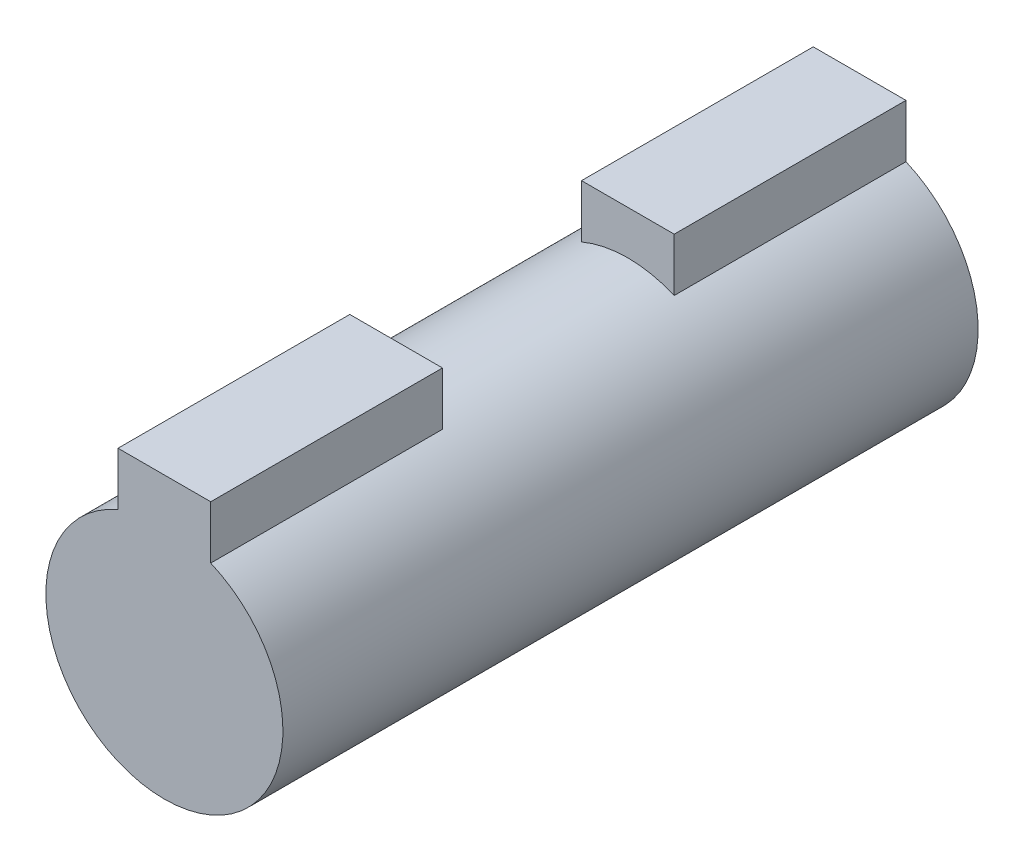
SolidWorks part; units mm, degrees
ref_plane "Front" through (0, 0, 0) normal (0, 0, 1) x (1, 0, 0)
ref_plane "Top" through (0, 0, 0) normal (0, 1, 0) x (1, 0, 0)
ref_plane "Right" through (0, 0, 0) normal (1, 0, 0) x (0, 0, -1)
sketch "Sketch1" plane through (0, 0, 0) normal (0, 0, 1) x (1, 0, 0)
  line L0 (0, 0) -> (0, 6.7866) construction
  line L2 (-2, 7) -> (2, 7)
  line L3 (-2, 7) -> (-2, 4.7072)
  line L5 (2, 7) -> (2, 4.7072)
  arc A0 (-2, 4.7072) -> (2, 4.7072) centre (0, 0) ccw
  point P5 (0, 0)
  point P8 (0, 0)
  dimension "D1" = 10.229
  dimension "D2" = 4
  dimension "D3" = 7
extrude "Boss-Extrude1" add sketch "Sketch1" along normal blind 30
sketch "Sketch2" plane through (0, 0, 30) normal (0, 0, 1) x (1, 0, 0)
  circle A1 centre (0, 0) radius 7.8
  circle A2 centre (0, 0) radius 5.1145
extrude "Cut-Extrude1" cut sketch "Sketch2" against normal blind 10 from offset 10
